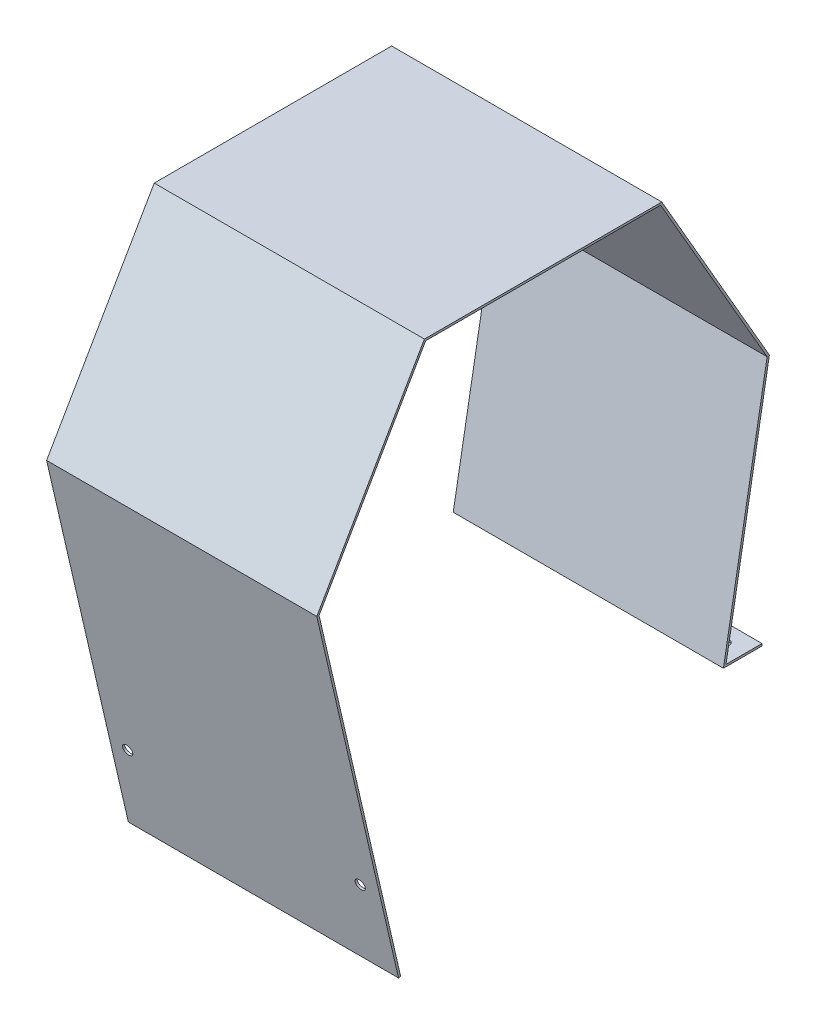
SolidWorks part; units mm, degrees
material "6061-T6 (SS)"
ref_plane "Front Plane" through (0, 0, 0) normal (0, 0, 1) x (1, 0, 0)
ref_plane "Top Plane" through (0, 0, 0) normal (0, 1, 0) x (1, 0, 0)
ref_plane "Right Plane" through (0, 0, 0) normal (1, 0, 0) x (0, 0, -1)
sketch "Sketch3" plane through (-16.1676, 0, 0) normal (1, 0, 0) x (0, 0, -1)
  line L0 (746.209, 603.4568) -> (886.209, 603.4568)
  line L1 (886.209, 603.4568) -> (949.709, 493.4716)
  line L2 (949.709, 493.4716) -> (923.6617, 345.7505)
  line L4 (923.6617, 345.7505) -> (946.6617, 345.7505)
  line L5 (746.209, 603.4568) -> (682.709, 493.4716)
  line L6 (682.709, 493.4716) -> (731.2984, 283.0077)
  line L7 (925.1753, 347.0205) -> (946.6617, 347.0205)
  line L8 (951.0399, 493.7063) -> (925.1753, 347.0205)
  line L9 (886.9422, 604.7268) -> (951.0399, 493.7063)
  line L10 (745.4757, 604.7268) -> (886.9422, 604.7268)
  line L11 (745.4757, 604.7268) -> (681.359, 493.6734)
  line L12 (681.359, 493.6734) -> (730.0609, 282.722)
  line L13 (946.6617, 347.0205) -> (946.6617, 345.7505)
  line L14 (731.2984, 283.0077) -> (730.0609, 282.722)
  line L15 (938.911, 345.6656) -> (932.9111, 345.699) construction
  circle A0 centre (817.329, 469) radius 114 construction
  dimension "D2" = 140
  dimension "D3" = 127
  dimension "D4" = 127
  dimension "D5" = 120
  dimension "D6" = 120
  dimension "D7" = 137
  dimension "D8" = 140
  dimension "D9" = 150
  dimension "D10" = 216
  dimension "D11" = 134.62
  dimension "D12" = 23
  dimension "D1" = 1.27
extrude "Boss-Extrude1" add sketch "Sketch3" along normal blind 97 and the other way blind 64
sketch "Sketch6" plane through (0, 347.0205, 0) normal (0, 1, 0) x (1, 0, 0)
  line L0 (-69.5, 1013.6443) -> (-69.5, 919.6071) construction
  line L2 (-80.1676, 935.9185) -> (-69.5, 935.9185) construction
  line L3 (-80.1676, 946.6617) -> (-80.1676, 925.1753) construction
  line L4 (69, 1016.4931) -> (69, 935.9185) construction
  circle A0 centre (-69.5, 935.9185) radius 3
  circle A1 centre (69, 935.9185) radius 3
  ellipse E0 centre (-69.5, 1016.8193) end of major axis (-66.325, 1016.8193) minor radius 3.175 construction
  ellipse E1 centre (69, 1020.4931) end of major axis (73, 1020.4931) minor radius 3.9999 construction
  dimension "D1" = 6
  dimension "D2" = 6
extrude "Cut-Extrude1" cut sketch "Sketch6" against normal blind 10
sketch "Sketch8" plane through (0, 174.3254, -755.0863) normal (0, -0.225, 0.9744) x (1, 0, 0)
  line L0 (-69.5, 86.4753) -> (-69.5, 204.4333) construction
  line L1 (69, 55.3656) -> (69, 204.4333) construction
  line L2 (80.5, 55.3656) -> (57.5, 55.3656) construction
  line L3 (-283.2736, 160.9475) -> (226.6722, 159.8694) construction
  circle A4 centre (69, 160.2027) radius 3
  circle A5 centre (-69.5, 160.4956) radius 3
  ellipse E0 centre (-69.5, 87.2068) end of major axis (-66.325, 87.2068) minor radius 0.7314 construction
  ellipse E1 centre (-69.5, 87.2068) end of major axis (-66.325, 87.2068) minor radius 0.7314 construction
extrude "Cut-Extrude3" cut sketch "Sketch8" against normal blind 10
